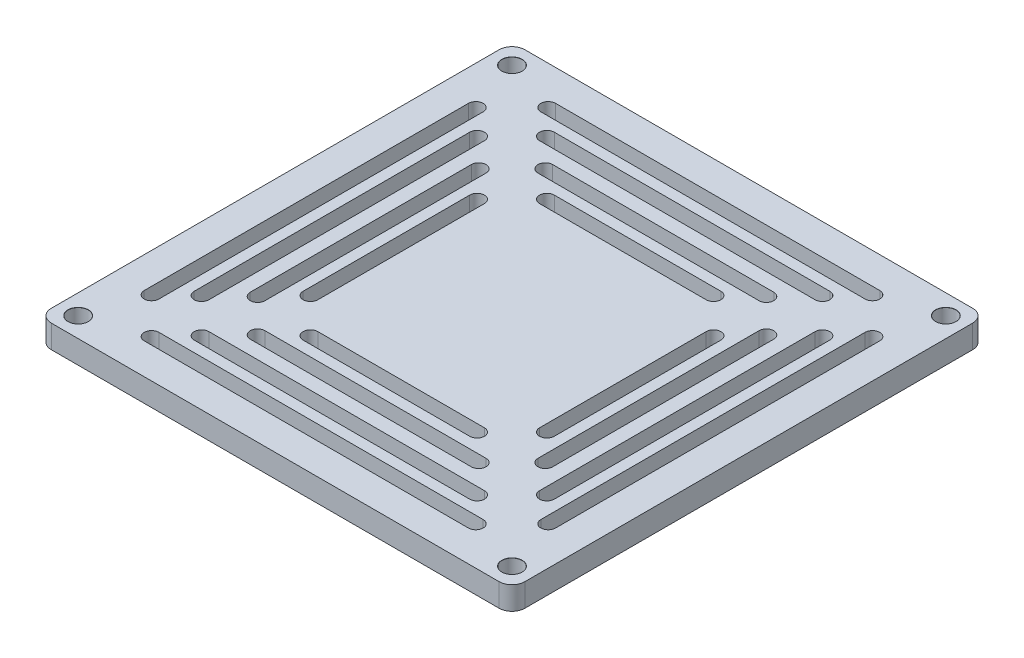
SolidWorks part; units mm, degrees
ref_plane "Front Plane" through (0, 0, 0) normal (0, 0, 1) x (1, 0, 0)
ref_plane "Top Plane" through (0, 0, 0) normal (0, 1, 0) x (1, 0, 0)
ref_plane "Right Plane" through (0, 0, 0) normal (1, 0, 0) x (0, 0, -1)
sketch "Sketch1" plane through (0, 0, 0) normal (0, 1, 0) x (1, 0, 0)
  line L1 (-46.9265, -46.9265) -> (46.9265, -46.9265)
  line L2 (-46.9265, -46.9265) -> (-46.9265, 46.9265)
  line L3 (-46.9265, 46.9265) -> (46.9265, 46.9265)
  line L4 (46.9265, -46.9265) -> (46.9265, 46.9265)
  line L5 (-46.9265, -46.9265) -> (46.9265, 46.9265) construction
  line L6 (-46.9265, 46.9265) -> (46.9265, -46.9265) construction
  point P0 (0, 0)
  dimension "D1" = 93.853
extrude "Boss-Extrude1" add sketch "Sketch1" along normal blind 4.572 contours L3 L4 L1 L2
sketch "Sketch3" plane through (0, 4.572, 0) normal (0, 1, 0) x (1, 0, 0)
  line L0 (-39.3065, -39.3065) -> (-39.3065, 39.3065) construction
  line L1 (-42.9895, -42.9895) -> (42.9895, -42.9895) construction
  line L2 (-42.9895, -42.9895) -> (-42.9895, 42.9895) construction
  line L3 (-42.9895, 42.9895) -> (42.9895, 42.9895) construction
  line L4 (42.9895, -42.9895) -> (42.9895, 42.9895) construction
  line L5 (-42.9895, -42.9895) -> (42.9895, 42.9895) construction
  line L6 (-42.9895, 42.9895) -> (42.9895, -42.9895) construction
  line L7 (-34.2265, -34.2265) -> (-34.2265, 34.2265) construction
  line L8 (-23.4315, -23.4315) -> (-23.4315, 23.4315) construction
  line L9 (-46.9265, -46.9265) -> (-46.9265, 46.9265) construction
  line L10 (-28.5115, -28.5115) -> (-28.5115, 28.5115) construction
  line L11 (-39.3065, -32.131) -> (-39.3065, 32.131) construction
  line L12 (-40.767, -32.131) -> (-40.767, 32.131)
  line L13 (-37.846, -32.131) -> (-37.846, 32.131)
  line L14 (0, 0) -> (-42.9895, 0) construction
  line L15 (-34.2265, -27.305) -> (-34.2265, 27.305) construction
  line L16 (-35.687, -27.305) -> (-35.687, 27.305)
  line L17 (-32.766, -27.305) -> (-32.766, 27.305)
  line L18 (-28.5115, -21.9075) -> (-28.5115, 21.9075) construction
  line L19 (-29.972, -21.9075) -> (-29.972, 21.9075)
  line L20 (-27.051, -21.9075) -> (-27.051, 21.9075)
  line L21 (-23.4315, -16.51) -> (-23.4315, 16.51) construction
  line L22 (-24.892, -16.51) -> (-24.892, 16.51)
  line L23 (-21.971, -16.51) -> (-21.971, 16.51)
  line L24 (-32.131, 37.846) -> (32.131, 37.846)
  line L25 (-32.131, 40.767) -> (32.131, 40.767)
  line L26 (-27.305, 32.766) -> (27.305, 32.766)
  line L27 (-27.305, 35.687) -> (27.305, 35.687)
  line L28 (-21.9075, 27.051) -> (21.9075, 27.051)
  line L29 (-21.9075, 29.972) -> (21.9075, 29.972)
  line L30 (-16.51, 21.971) -> (16.51, 21.971)
  line L31 (-16.51, 24.892) -> (16.51, 24.892)
  line L32 (-32.131, 39.3065) -> (32.131, 39.3065) construction
  line L33 (-27.305, 34.2265) -> (27.305, 34.2265) construction
  line L34 (-21.9075, 28.5115) -> (21.9075, 28.5115) construction
  line L35 (-16.51, 23.4315) -> (16.51, 23.4315) construction
  line L36 (37.846, 32.131) -> (37.846, -32.131)
  line L37 (40.767, 32.131) -> (40.767, -32.131)
  line L38 (32.766, 27.305) -> (32.766, -27.305)
  line L39 (35.687, 27.305) -> (35.687, -27.305)
  line L40 (27.051, 21.9075) -> (27.051, -21.9075)
  line L41 (29.972, 21.9075) -> (29.972, -21.9075)
  line L42 (21.971, 16.51) -> (21.971, -16.51)
  line L43 (24.892, 16.51) -> (24.892, -16.51)
  line L44 (39.3065, 32.131) -> (39.3065, -32.131) construction
  line L45 (34.2265, 27.305) -> (34.2265, -27.305) construction
  line L46 (28.5115, 21.9075) -> (28.5115, -21.9075) construction
  line L47 (23.4315, 16.51) -> (23.4315, -16.51) construction
  line L48 (32.131, -37.846) -> (-32.131, -37.846)
  line L49 (32.131, -40.767) -> (-32.131, -40.767)
  line L50 (27.305, -32.766) -> (-27.305, -32.766)
  line L51 (27.305, -35.687) -> (-27.305, -35.687)
  line L52 (21.9075, -27.051) -> (-21.9075, -27.051)
  line L53 (21.9075, -29.972) -> (-21.9075, -29.972)
  line L54 (16.51, -21.971) -> (-16.51, -21.971)
  line L55 (16.51, -24.892) -> (-16.51, -24.892)
  line L56 (32.131, -39.3065) -> (-32.131, -39.3065) construction
  line L57 (27.305, -34.2265) -> (-27.305, -34.2265) construction
  line L58 (21.9075, -28.5115) -> (-21.9075, -28.5115) construction
  line L59 (16.51, -23.4315) -> (-16.51, -23.4315) construction
  arc A0 (-40.767, -32.131) -> (-37.846, -32.131) centre (-39.3065, -32.131) ccw
  arc A1 (-37.846, 32.131) -> (-40.767, 32.131) centre (-39.3065, 32.131) ccw
  arc A2 (-35.687, -27.305) -> (-32.766, -27.305) centre (-34.2265, -27.305) ccw
  arc A3 (-32.766, 27.305) -> (-35.687, 27.305) centre (-34.2265, 27.305) ccw
  arc A4 (-29.972, -21.9075) -> (-27.051, -21.9075) centre (-28.5115, -21.9075) ccw
  arc A5 (-27.051, 21.9075) -> (-29.972, 21.9075) centre (-28.5115, 21.9075) ccw
  arc A6 (-24.892, -16.51) -> (-21.971, -16.51) centre (-23.4315, -16.51) ccw
  arc A7 (-21.971, 16.51) -> (-24.892, 16.51) centre (-23.4315, 16.51) ccw
  arc A8 (-32.131, 40.767) -> (-32.131, 37.846) centre (-32.131, 39.3065) ccw
  arc A9 (32.131, 37.846) -> (32.131, 40.767) centre (32.131, 39.3065) ccw
  arc A10 (-27.305, 35.687) -> (-27.305, 32.766) centre (-27.305, 34.2265) ccw
  arc A11 (27.305, 32.766) -> (27.305, 35.687) centre (27.305, 34.2265) ccw
  arc A12 (-21.9075, 29.972) -> (-21.9075, 27.051) centre (-21.9075, 28.5115) ccw
  arc A13 (21.9075, 27.051) -> (21.9075, 29.972) centre (21.9075, 28.5115) ccw
  arc A14 (-16.51, 24.892) -> (-16.51, 21.971) centre (-16.51, 23.4315) ccw
  arc A15 (16.51, 21.971) -> (16.51, 24.892) centre (16.51, 23.4315) ccw
  arc A16 (40.767, 32.131) -> (37.846, 32.131) centre (39.3065, 32.131) ccw
  arc A17 (37.846, -32.131) -> (40.767, -32.131) centre (39.3065, -32.131) ccw
  arc A18 (35.687, 27.305) -> (32.766, 27.305) centre (34.2265, 27.305) ccw
  arc A19 (32.766, -27.305) -> (35.687, -27.305) centre (34.2265, -27.305) ccw
  arc A20 (29.972, 21.9075) -> (27.051, 21.9075) centre (28.5115, 21.9075) ccw
  arc A21 (27.051, -21.9075) -> (29.972, -21.9075) centre (28.5115, -21.9075) ccw
  arc A22 (24.892, 16.51) -> (21.971, 16.51) centre (23.4315, 16.51) ccw
  arc A23 (21.971, -16.51) -> (24.892, -16.51) centre (23.4315, -16.51) ccw
  arc A24 (32.131, -40.767) -> (32.131, -37.846) centre (32.131, -39.3065) ccw
  arc A25 (-32.131, -37.846) -> (-32.131, -40.767) centre (-32.131, -39.3065) ccw
  arc A26 (27.305, -35.687) -> (27.305, -32.766) centre (27.305, -34.2265) ccw
  arc A27 (-27.305, -32.766) -> (-27.305, -35.687) centre (-27.305, -34.2265) ccw
  arc A28 (21.9075, -29.972) -> (21.9075, -27.051) centre (21.9075, -28.5115) ccw
  arc A29 (-21.9075, -27.051) -> (-21.9075, -29.972) centre (-21.9075, -28.5115) ccw
  arc A30 (16.51, -24.892) -> (16.51, -21.971) centre (16.51, -23.4315) ccw
  arc A31 (-16.51, -21.971) -> (-16.51, -24.892) centre (-16.51, -23.4315) ccw
  point P0 (0, 0)
  point P19 (-39.3065, 0)
  point P26 (-34.2265, 0)
  point P32 (-28.5115, 0)
  point P39 (-23.4315, 0)
  point P52 (0, 39.3065)
  point P57 (0, 34.2265)
  point P63 (0, 28.5115)
  point P70 (0, 23.4315)
  point P80 (39.3065, 0)
  point P85 (34.2265, 0)
  point P91 (28.5115, 0)
  point P98 (23.4315, 0)
  point P108 (0, -39.3065)
  point P113 (0, -34.2265)
  point P119 (0, -28.5115)
  point P126 (0, -23.4315)
  point P133 (0, 0)
  dimension "D1" = 85.979
  dimension "D2" = 7.62
  dimension "D3" = 12.7
  dimension "D4" = 23.495
  dimension "D5" = 18.415
  dimension "D6" = 2.921
  dimension "D7" = 64.262
  dimension "D8" = 2.921
  dimension "D9" = 54.61
  dimension "D10" = 2.921
  dimension "D11" = 43.815
  dimension "D12" = 2.921
  dimension "D13" = 33.02
  dimension "D14" = 4
extrude "Cut-Extrude1" cut sketch "Sketch3" against normal through all contours L17 A3 L16 A2 | L20 A5 L19 A4 | L23 A7 L22 A6 | L30 A15 L31 A14 | L28 A13 L29 A12 | L26 A11 L27 A10 | L24 A9 L25 A8 | L42 A23 L43 A22 | L40 A21 L41 A20 | L38 A19 L39 A18 | L36 A17 L37 A16 | L54 A31 L55 A30 | L52 A29 L53 A28 | L50 A27 L51 A26 | L48 A25 L49 A24 | L12 A1 L13 A0
hole_wizard "Ø4.0mm Dowel Hole1" positions "3DSketch1" profile "Sketch4" hole size "Ø4.0" standard "ANSI Metric" end condition through all
sketch3d "3DSketch1"
  point P0 (-42.9895, 4.572, 42.9895)
  point P3 (-42.9895, 4.572, -42.9895)
  point P6 (42.9895, 4.572, -42.9895)
  point P9 (42.9895, 4.572, 42.9895)
sketch "Sketch4" plane through (-42.9895, 4.572, 42.9895) normal (1, 0, 0) x (0, 0, 1)
  line L0 (0, 0) -> (0, 4.572)
  line L1 (0, 4.572) -> (2, 4.572)
  line L2 (2, 4.572) -> (2, 0.025)
  line L3 (2, 0.025) -> (2.025, 0)
  line L5 (2.025, 0) -> (0, 0)
  line L6 (-2, 0.025) -> (-2.025, 0) construction
  line L11 (0, -6.35) -> (0, 107.95) construction
  dimension "Thru Hole Dia." = 4
  dimension "Thru Hole Depth" = 4.572
  dimension "Near C'Sink Dia." = 4.05
  dimension "Near C'Sink Angle" = 90
fillet "Fillet2" radius 2.54 4 edges at (-46.9265, 2.286, 46.9265) (-46.9265, 2.286, -46.9265) (46.9265, 2.286, -46.9265) (46.9265, 2.286, 46.9265)
equation "\"D8@Sketch3\"=\"D6@Sketch3\""
equation "\"D10@Sketch3\"=\"D6@Sketch3\""
equation "\"D12@Sketch3\"=\"D6@Sketch3\""
